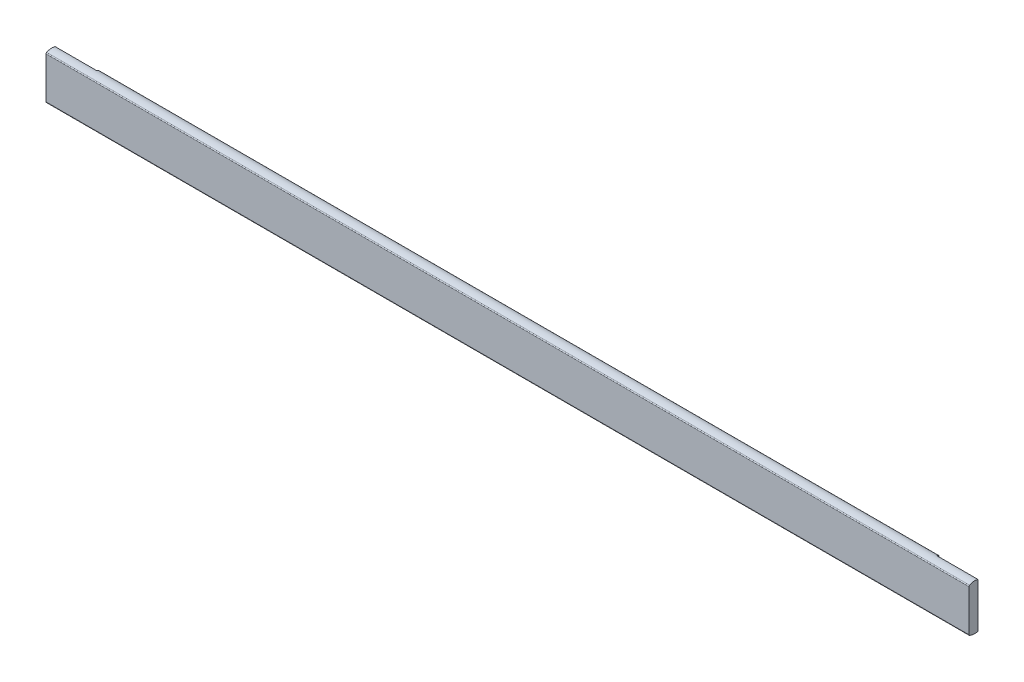
SolidWorks part; units mm, degrees
ref_plane "Front Plane" through (0, 0, 0) normal (0, 0, 1) x (1, 0, 0)
ref_plane "Top Plane" through (0, 0, 0) normal (0, 1, 0) x (1, 0, 0)
ref_plane "Right Plane" through (0, 0, 0) normal (1, 0, 0) x (0, 0, -1)
sketch "Sketch1" plane through (0, 0, 0) normal (1, 0, 0) x (0, 0, -1)
  line L0 (-12.7, 0) -> (0, 0) construction
  line L1 (12.7, -50.8) -> (-12.7, -50.8)
  line L2 (12.7, -50.8) -> (12.7, 50.8)
  line L3 (12.7, 50.8) -> (-12.7, 50.8)
  line L4 (-12.7, -50.8) -> (-12.7, 50.8)
  line L5 (12.7, -50.8) -> (-12.7, 50.8) construction
  line L6 (12.7, 50.8) -> (-12.7, -50.8) construction
  arc A0 (-12.7, 47.397) -> (12.7, 47.397) centre (0, 25.4) cw
  arc A1 (-12.7, -47.397) -> (12.7, -47.397) centre (0, -25.4) ccw
  point P0 (0, 0)
  dimension "D3" = 25.4
  dimension "D1" = 101.6
  dimension "D2" = 25.4
extrude "Boss-Extrude2" add sketch "Sketch1" along normal mid plane 2042.16 contours L4 A1 L2 A0
fillet "Fillet1" radius 2.54 4 edges at (0, -47.397, 12.7) (0, -47.397, -12.7) (0, 47.397, -12.7) (0, 47.397, 12.7)
sketch "Sketch2" plane through (0, 0, 0) normal (0, 1, 0) x (1, 0, 0)
  line L0 (0, 0) -> (0, 11.2889) construction
  line L1 (1021.08, 12.7) -> (929.64, 12.7)
  line L2 (1021.08, 12.7) -> (1021.08, 7.62)
  line L3 (1021.08, 7.62) -> (929.64, 7.62)
  line L4 (929.64, 12.7) -> (929.64, 7.62)
  line L5 (1021.08, 11.2889) -> (-1021.08, 11.2889) construction
  line L6 (-929.64, 12.7) -> (-929.64, 7.62)
  line L7 (-1021.08, 7.62) -> (-929.64, 7.62)
  line L8 (-1021.08, 12.7) -> (-1021.08, 7.62)
  line L9 (-1021.08, 12.7) -> (-929.64, 12.7)
  dimension "D1" = 91.44
  dimension "D2" = 5.08
extrude "Cut-Extrude1" cut sketch "Sketch2" against normal through all both and the other way through all
